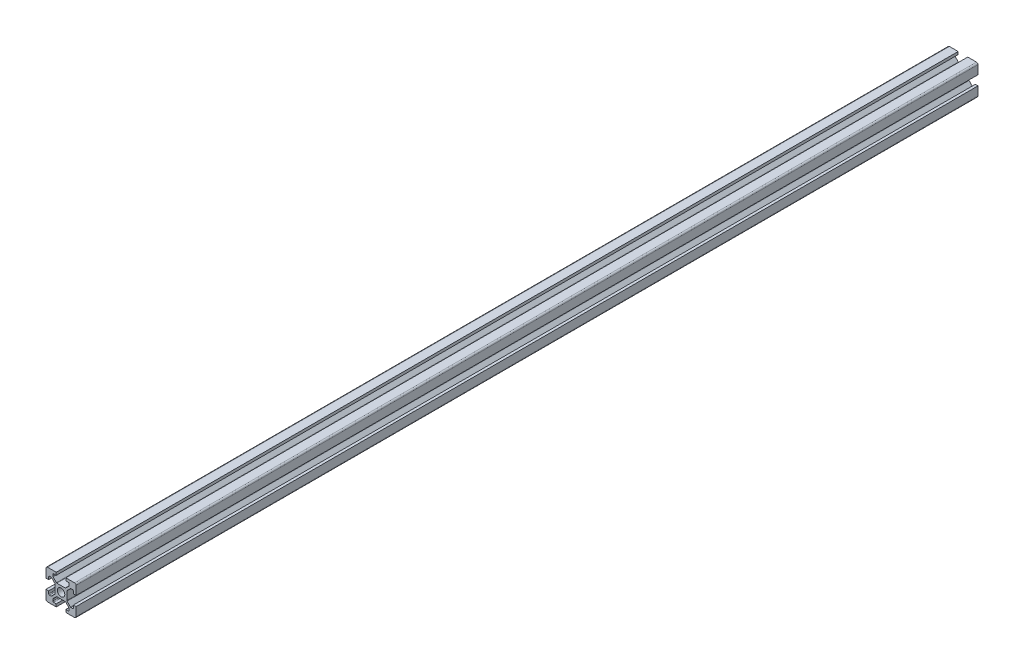
SolidWorks part; units mm, degrees
material "1060 Alloy"
ref_plane "Front Plane" through (0, 0, 0) normal (0, 0, 1) x (1, 0, 0)
ref_plane "Top Plane" through (0, 0, 0) normal (0, 1, 0) x (1, 0, 0)
ref_plane "Right Plane" through (0, 0, 0) normal (1, 0, 0) x (0, 0, -1)
sketch "Sketch1" plane through (0, 0, 0) normal (0, 0, 1) x (1, 0, 0)
  line L0 (20, 0) -> (-8.059, 28.059) construction
  line L1 (0, 0) -> (6.8, 0)
  line L2 (0, 0) -> (0, 6.8)
  line L3 (0, 20) -> (6.8, 20)
  line L4 (20, 0) -> (20, 6.8)
  line L5 (6.8, 20) -> (6.8, 18.2)
  line L6 (20, 20) -> (8.2322, 8.2322) construction
  line L7 (12.95, 6.1) -> (7.05, 6.1)
  line L8 (13.9, 7.05) -> (13.9, 12.95)
  line L9 (12.95, 13.9) -> (7.05, 13.9)
  line L10 (6.1, 7.05) -> (6.1, 12.95)
  line L11 (13.9, 6.1) -> (6.1, 13.9) construction
  line L12 (13.9, 13.9) -> (6.1, 6.1) construction
  line L13 (4.55, 16.4) -> (7.05, 13.9)
  line L14 (13.2, 18.2) -> (13.2, 20)
  line L15 (1.8, 6.8) -> (0, 6.8)
  line L16 (0, 13.2) -> (0, 20)
  line L17 (0, 13.2) -> (1.8, 13.2)
  line L18 (10, 10) -> (10, 13.9) construction
  line L19 (16.4, 4.55) -> (13.9, 7.05)
  line L20 (4.55, 16.4) -> (4.55, 18.2)
  line L21 (4.55, 18.2) -> (6.8, 18.2)
  line L22 (13.2, 18.2) -> (15.45, 18.2)
  line L23 (15.45, 18.2) -> (15.45, 16.4)
  line L24 (15.45, 16.4) -> (12.95, 13.9)
  line L25 (16.4, 4.55) -> (18.2, 4.55)
  line L26 (18.2, 4.55) -> (18.2, 6.8)
  line L27 (20, 6.8) -> (18.2, 6.8)
  line L28 (18.2, 13.2) -> (20, 13.2)
  line L29 (18.2, 13.2) -> (18.2, 15.45)
  line L30 (18.2, 15.45) -> (16.4, 15.45)
  line L31 (16.4, 15.45) -> (13.9, 12.95)
  line L32 (1.8, 4.55) -> (3.6, 4.55)
  line L33 (3.6, 15.45) -> (6.1, 12.95)
  line L34 (3.6, 15.45) -> (1.8, 15.45)
  line L35 (1.8, 15.45) -> (1.8, 13.2)
  line L36 (0, 13.2) -> (1.8, 13.2)
  line L37 (1.8, 6.8) -> (0, 6.8)
  line L38 (3.6, 4.55) -> (6.1, 7.05)
  line L39 (1.8, 6.8) -> (1.8, 4.55)
  line L40 (15.45, 3.6) -> (12.95, 6.1)
  line L41 (4.55, 3.6) -> (7.05, 6.1)
  line L42 (4.55, 1.8) -> (4.55, 3.6)
  line L43 (6.8, 1.8) -> (4.55, 1.8)
  line L44 (6.8, 1.8) -> (6.8, 0)
  line L45 (15.45, 3.6) -> (15.45, 1.8)
  line L46 (15.45, 1.8) -> (13.2, 1.8)
  line L47 (13.2, 0) -> (13.2, 1.8)
  line L48 (13.2, 20) -> (20, 20)
  line L49 (20, 13.2) -> (20, 20)
  line L50 (13.2, 0) -> (20, 0)
  line L51 (6.1, 6.1) -> (-5.5045, -5.5045) construction
  circle A0 centre (10, 10) radius 2.5
  point P25 (10, 16.4)
  point P39 (13.2, 19.1)
  point P46 (0.9, 6.8)
  dimension "D3" = 5
  dimension "D2" = 20
  dimension "D4" = 7.8
  dimension "D5" = 7.8
  dimension "D6" = 6.8
  dimension "D7" = 6.8
  dimension "D8" = 1.8
  dimension "D9" = 10.9
  dimension "D10" = 1.8
  dimension "D11" = 10.9
  dimension "D12" = 20
extrude "Boss-Extrude1" add sketch "Sketch1" along normal blind 600 contours L47 L50 L4 L27 L26 L25 L19 L8 L31 L30 L29 L28 L49 L48 L14 L22 L23 L24 L9 L13 L20 L21 L5 L3 L16 L17 L35 L34 L33 L10 L38 L32 L39 L15 L2 L1 L44 L43 L42 L41 L7 L40 L45 L46 A0
fillet "Fillet1" radius 1 4 edges at (20, 20, 300) (20, 0, 300) (0, 0, 300) (0, 20, 300)
fillet "Fillet2" radius 0.5 6 edges at (4.55, 18.2, 300) (4.55, 16.4, 300) (7.05, 13.9, 300) (15.45, 18.2, 300) (15.45, 16.4, 300) (12.95, 13.9, 300)
fillet "Fillet3" radius 0.5 6 edges at (18.2, 15.45, 300) (16.4, 15.45, 300) (13.9, 12.95, 300) (18.2, 4.55, 300) (13.9, 7.05, 300) (16.4, 4.55, 300)
fillet "Fillet4" radius 0.5 6 edges at (1.8, 15.45, 300) (3.6, 15.45, 300) (6.1, 12.95, 300) (3.6, 4.55, 300) (1.8, 4.55, 300) (6.1, 7.05, 300)
fillet "Fillet5" radius 0.5 6 edges at (7.05, 6.1, 300) (4.55, 3.6, 300) (4.55, 1.8, 300) (15.45, 1.8, 300) (15.45, 3.6, 300) (12.95, 6.1, 300)
